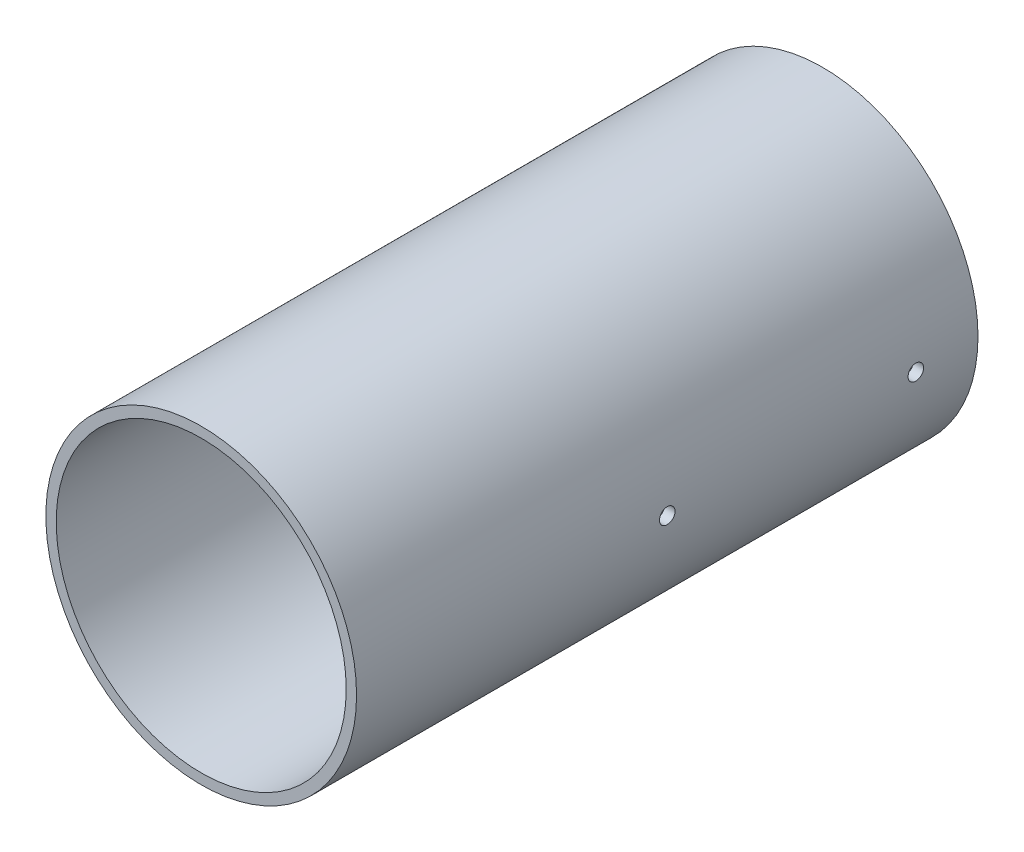
SolidWorks part; units mm, degrees
ref_plane "Front Plane" through (0, 0, 0) normal (0, 0, 1) x (1, 0, 0)
ref_plane "Top Plane" through (0, 0, 0) normal (0, 1, 0) x (1, 0, 0)
ref_plane "Right Plane" through (0, 0, 0) normal (1, 0, 0) x (0, 0, -1)
sketch "Sketch1" plane through (0, 0, 0) normal (0, 0, 1) x (1, 0, 0)
  circle A0 centre (0, 0) radius 30
  circle A1 centre (0, 0) radius 28
  dimension "D1" = 60
  dimension "D2" = 2
extrude "Boss-Extrude1" add sketch "Sketch1" along normal blind 120
sketch "Sketch2" plane through (0, 0, 0) normal (1, 0, 0) x (0, 0, -1)
  line L0 (0, 0) -> (-120, 0) construction
  line L1 (-120, 30) -> (-120, -30) construction
  line L2 (-120, 0) -> (0, 0) construction
  circle A0 centre (-12, 0) radius 1.5
  circle A1 centre (-60, 0) radius 1.5
  dimension "D1" = 3
  dimension "D2" = 48
extrude "Cut-Extrude1" cut sketch "Sketch2" against normal through all both and the other way through all
